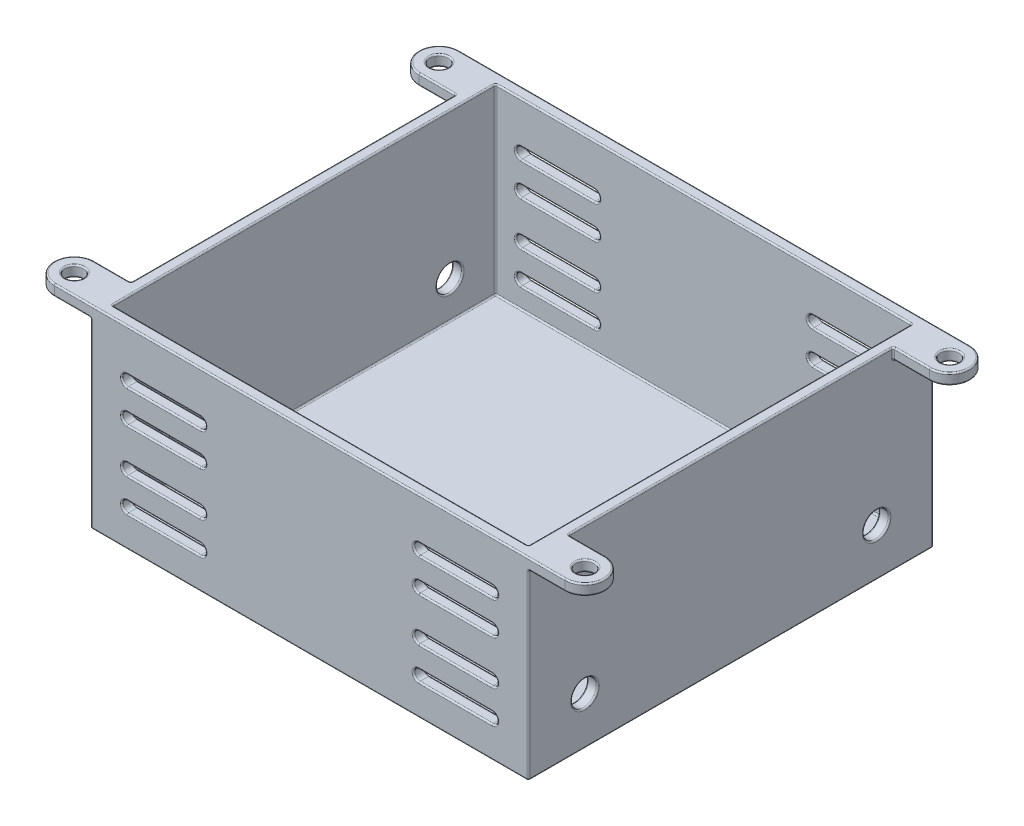
SolidWorks part; units mm, degrees
ref_plane "Front Plane" through (0, 0, 0) normal (0, 0, 1) x (1, 0, 0)
ref_plane "Top Plane" through (0, 0, 0) normal (0, 1, 0) x (1, 0, 0)
ref_plane "Right Plane" through (0, 0, 0) normal (1, 0, 0) x (0, 0, -1)
sketch "Sketch1" plane through (0, 0, 0) normal (0, 1, 0) x (1, 0, 0)
  line L0 (-35, 27.75) -> (35, 27.75) construction
  line L1 (-35, -25) -> (35, -25) construction
  line L2 (-35, -25) -> (-35, 25) construction
  line L3 (-35, 25) -> (35, 25) construction
  line L4 (35, -25) -> (35, 25) construction
  line L5 (-35, -25) -> (35, 25) construction
  line L6 (-35, 25) -> (35, -25) construction
  line L7 (-30, 27.75) -> (-30, -27.75)
  line L8 (-30, -27.75) -> (30, -27.75)
  line L9 (-35, -27.75) -> (35, -27.75) construction
  line L10 (30, -27.75) -> (30, 27.75)
  line L11 (30, 27.75) -> (-30, 27.75)
  line L12 (-35, 22.25) -> (-30, 22.25)
  line L13 (35, 22.25) -> (30, 22.25)
  line L14 (35, -22.25) -> (30, -22.25)
  line L15 (-35, -22.25) -> (-30, -22.25)
  circle A0 centre (-35, 25) radius 1.25
  circle A1 centre (-35, -25) radius 1.25
  circle A2 centre (35, -25) radius 1.25
  circle A3 centre (35, 25) radius 1.25
  circle A4 centre (-35, 25) radius 2.75
  circle A5 centre (35, 25) radius 2.75
  circle A6 centre (35, -25) radius 2.75
  circle A7 centre (-35, -25) radius 2.75
  point P0 (0, 0)
  point P22 (0, 27.75)
  dimension "D3" = 2.5
  dimension "D1" = 70
  dimension "D2" = 50
  dimension "D5" = 60
  dimension "D4" = 1.5
sketch "Sketch2" plane through (0, 0, 0) normal (0, 1, 0) x (1, 0, 0)
  line L0 (-30, -27.75) -> (30, -27.75) construction
  line L1 (30, -27.75) -> (30, 27.75) construction
  line L2 (-30, 27.75) -> (-30, -27.75) construction
  line L3 (30, 27.75) -> (-30, 27.75) construction
  line L4 (-30, -27.75) -> (30, -27.75)
  line L5 (30, -27.75) -> (30, 27.75)
  line L6 (-30, 27.75) -> (-30, -27.75)
  line L7 (30, 27.75) -> (-30, 27.75)
  line L8 (28.5, 26.25) -> (-28.5, 26.25)
  line L9 (-28.5, 26.25) -> (-28.5, -26.25)
  line L10 (-28.5, -26.25) -> (28.5, -26.25)
  line L11 (28.5, -26.25) -> (28.5, 26.25)
  dimension "D1" = 1.5
extrude "Boss-Extrude1" add sketch "Sketch2" against normal blind 25
sketch "Sketch3" plane through (0, -25, 0) normal (0, -1, 0) x (1, 0, 0)
  line L4 (-30, 27.75) -> (-30, -27.75)
  line L5 (-30, -27.75) -> (30, -27.75)
  line L6 (30, -27.75) -> (30, 27.75)
  line L7 (30, 27.75) -> (-30, 27.75)
  line L8 (-30, 27.75) -> (-30, -27.75)
  line L9 (-30, -27.75) -> (30, -27.75)
  line L10 (30, -27.75) -> (30, 27.75)
  line L11 (30, 27.75) -> (-30, 27.75)
  dimension "D1" = 0
extrude "Boss-Extrude2" add sketch "Sketch3" along normal blind 1.5
sketch "Sketch4" plane through (0, 0, 0) normal (0, 1, 0) x (1, 0, 0)
  line L0 (-35, -22.25) -> (-30, -22.25) construction
  line L1 (35, 22.25) -> (30, 22.25) construction
  line L2 (-35, 22.25) -> (-30, 22.25) construction
  line L3 (35, -22.25) -> (30, -22.25) construction
  line L4 (-30, 27.75) -> (-30, -27.75)
  line L5 (-30, -27.75) -> (30, -27.75)
  line L6 (30, -27.75) -> (30, 27.75)
  line L7 (30, 27.75) -> (-30, 27.75)
  line L8 (-30, 27.75) -> (-30, 22.25)
  line L10 (30, -27.75) -> (30, -22.25)
  line L12 (-35, -22.25) -> (-30, -22.25)
  line L13 (35, 22.25) -> (30, 22.25)
  line L14 (-35, 22.25) -> (-30, 22.25)
  line L15 (35, -22.25) -> (30, -22.25)
  line L16 (-35, 27.75) -> (35, 27.75) construction
  line L17 (-35, 27.75) -> (-30, 27.75)
  line L18 (-35, -27.75) -> (35, -27.75) construction
  line L19 (-35, -27.75) -> (-30, -27.75)
  line L20 (30, 22.25) -> (30, 27.75)
  line L21 (-30, -22.25) -> (-30, -27.75)
  line L22 (30, -27.75) -> (35, -27.75)
  line L23 (30, 27.75) -> (35, 27.75)
  circle A1 centre (35, -25) radius 2.75
  arc A2 (35, -27.75) -> (35, -22.25) centre (35, -25) ccw
  circle A3 centre (35, 25) radius 2.75
  arc A4 (35, 22.25) -> (35, 27.75) centre (35, 25) ccw
  circle A5 centre (-35, 25) radius 2.75
  arc A6 (-35, 27.75) -> (-35, 22.25) centre (-35, 25) ccw
  circle A7 centre (35, 25) radius 1.25
  circle A8 centre (35, 25) radius 1.25
  circle A9 centre (35, -25) radius 1.25
  circle A10 centre (35, -25) radius 1.25
  circle A11 centre (-35, -25) radius 1.25
  circle A12 centre (-35, -25) radius 1.25
  circle A13 centre (-35, 25) radius 1.25
  circle A14 centre (-35, 25) radius 1.25
  circle A15 centre (-35, -25) radius 2.75
  arc A16 (-35, -22.25) -> (-35, -27.75) centre (-35, -25) ccw
  dimension "D1" = 0
  dimension "D2" = 0
  dimension "D3" = 0
  dimension "D4" = 0
  dimension "D5" = 0
  dimension "D6" = 0
  dimension "D7" = 0
  dimension "D8" = 0
  dimension "D9" = 0
extrude "Boss-Extrude3" add sketch "Sketch4" against normal blind 1.5
sketch "Sketch5" plane through (0, 0, 0) normal (0, 0, 1) x (1, 0, 0)
  line L0 (30, -14) -> (-30, -14) construction
  line L1 (30, -26.5) -> (30, -1.5) construction
  line L2 (-30, -26.5) -> (-30, -1.5) construction
  line L3 (-25, -6.5) -> (-15, -6.5) construction
  line L4 (-25, -5.75) -> (-15, -5.75)
  line L5 (-25, -7.25) -> (-15, -7.25)
  line L6 (-25, -11) -> (-15, -11) construction
  line L7 (-25, -10.25) -> (-15, -10.25)
  line L8 (-25, -11.75) -> (-15, -11.75)
  line L9 (0, -14) -> (0, -20.2877) construction
  line L10 (25, -6.5) -> (15, -6.5) construction
  line L11 (25, -5.75) -> (15, -5.75)
  line L12 (25, -7.25) -> (15, -7.25)
  line L13 (25, -11) -> (15, -11) construction
  line L14 (25, -10.25) -> (15, -10.25)
  line L15 (25, -11.75) -> (15, -11.75)
  line L16 (25, -17) -> (15, -17) construction
  line L17 (25, -17.75) -> (15, -17.75)
  line L18 (25, -16.25) -> (15, -16.25)
  line L19 (-25, -17) -> (-15, -17) construction
  line L20 (-25, -17.75) -> (-15, -17.75)
  line L21 (-25, -16.25) -> (-15, -16.25)
  line L22 (25, -21.5) -> (15, -21.5) construction
  line L23 (25, -22.25) -> (15, -22.25)
  line L24 (25, -20.75) -> (15, -20.75)
  line L25 (-25, -21.5) -> (-15, -21.5) construction
  line L26 (-25, -22.25) -> (-15, -22.25)
  line L27 (-25, -20.75) -> (-15, -20.75)
  arc A0 (-25, -5.75) -> (-25, -7.25) centre (-25, -6.5) ccw
  arc A1 (-15, -7.25) -> (-15, -5.75) centre (-15, -6.5) ccw
  arc A2 (-25, -10.25) -> (-25, -11.75) centre (-25, -11) ccw
  arc A3 (-15, -11.75) -> (-15, -10.25) centre (-15, -11) ccw
  arc A4 (25, -5.75) -> (25, -7.25) centre (25, -6.5) cw
  arc A5 (15, -7.25) -> (15, -5.75) centre (15, -6.5) cw
  arc A6 (25, -10.25) -> (25, -11.75) centre (25, -11) cw
  arc A7 (15, -11.75) -> (15, -10.25) centre (15, -11) cw
  arc A8 (25, -17.75) -> (25, -16.25) centre (25, -17) ccw
  arc A9 (15, -16.25) -> (15, -17.75) centre (15, -17) ccw
  arc A10 (-25, -17.75) -> (-25, -16.25) centre (-25, -17) cw
  arc A11 (-15, -16.25) -> (-15, -17.75) centre (-15, -17) cw
  arc A12 (25, -22.25) -> (25, -20.75) centre (25, -21.5) ccw
  arc A13 (15, -20.75) -> (15, -22.25) centre (15, -21.5) ccw
  arc A14 (-25, -22.25) -> (-25, -20.75) centre (-25, -21.5) cw
  arc A15 (-15, -20.75) -> (-15, -22.25) centre (-15, -21.5) cw
  point P8 (-20, -6.5)
  point P16 (-20, -11)
  point P25 (20, -6.5)
  point P32 (20, -11)
  point P39 (20, -17)
  point P46 (-20, -17)
  point P53 (20, -21.5)
  point P60 (-20, -21.5)
  dimension "D1" = 10
  dimension "D2" = 1.5
  dimension "D3" = 20
  dimension "D4" = 7.5
  dimension "D5" = 4.5
extrude "Cut-Extrude4" cut sketch "Sketch5" along normal blind 53.5 and the other way blind 34.5
sketch "Sketch6" plane through (30, 0, 0) normal (1, 0, 0) x (0, 0, -1)
  line L0 (0, 0) -> (0, -20) construction
  line L1 (0, -20) -> (-20, -20) construction
  circle A0 centre (-20, -20) radius 1.75
  circle A1 centre (20, -20) radius 1.75
  dimension "D1" = 3.5
  dimension "D2" = 20
  dimension "D3" = 20
extrude "Cut-Extrude5" cut sketch "Sketch6" against normal blind 73.5
fillet "Fillet1" radius 0.2 196 edges at (30, -20, -18.25) (30, -20, 18.25) (-28.5, -20, -18.25) (28.5, -20, -21.75) (-30, -20, -18.25) (-28.5, -20, 21.75) (28.5, -20, 18.25) (-30, -20, 21.75) (-20, -7.25, 26.25) (-20, -7.25, 27.75) (-20, -7.25, -27.75) (-14.25, -6.5, 26.25) (-14.25, -6.5, 27.75) (-14.25, -6.5, -27.75) (-20, -5.75, 26.25) (-20, -5.75, 27.75) (-20, -5.75, -27.75) (-25.75, -6.5, 26.25) (-25.75, -6.5, 27.75) (-25.75, -6.5, -27.75) (-20, -17.75, 26.25) (-20, -17.75, 27.75) (-20, -17.75, -27.75) (-14.25, -17, 26.25) (-14.25, -17, 27.75) (-14.25, -17, -27.75) (-20, -16.25, 26.25) (-20, -16.25, 27.75) (-20, -16.25, -27.75) (-25.75, -17, 26.25) (-25.75, -17, 27.75) (-25.75, -17, -27.75) (20, -20.75, 26.25) (20, -20.75, 27.75) (20, -20.75, -27.75) (14.25, -21.5, 26.25) (14.25, -21.5, 27.75) (14.25, -21.5, -27.75) (20, -22.25, 26.25) (20, -22.25, 27.75) (20, -22.25, -27.75) (25.75, -21.5, 26.25) (25.75, -21.5, 27.75) (25.75, -21.5, -27.75) (-20, -22.25, 26.25) (-20, -22.25, 27.75) (-20, -22.25, -27.75) (-14.25, -21.5, 26.25) (-14.25, -21.5, 27.75) (-14.25, -21.5, -27.75) (-20, -20.75, 26.25) (-20, -20.75, 27.75) (-20, -20.75, -27.75) (-25.75, -21.5, 26.25) (-25.75, -21.5, 27.75) (-25.75, -21.5, -27.75) (-20, -11.75, 26.25) (-20, -11.75, 27.75) (-20, -11.75, -27.75) (-14.25, -11, 26.25) (-14.25, -11, 27.75) (-14.25, -11, -27.75) (-20, -10.25, 26.25) (-20, -10.25, 27.75) (-20, -10.25, -27.75) (-25.75, -11, 26.25) (-25.75, -11, 27.75) (-25.75, -11, -27.75) (20, -5.75, 26.25) (20, -5.75, 27.75) (20, -5.75, -27.75) (14.25, -6.5, 26.25) (14.25, -6.5, 27.75) (14.25, -6.5, -27.75) (20, -7.25, 26.25) (20, -7.25, 27.75) (20, -7.25, -27.75) (25.75, -6.5, 26.25) (25.75, -6.5, 27.75) (25.75, -6.5, -27.75) (20, -10.25, 26.25) (20, -10.25, 27.75) (20, -10.25, -27.75) (14.25, -11, 26.25) (14.25, -11, 27.75) (14.25, -11, -27.75) (20, -11.75, 26.25) (20, -11.75, 27.75) (20, -11.75, -27.75) (25.75, -11, 26.25) (25.75, -11, 27.75) (25.75, -11, -27.75) (20, -16.25, 26.25) (20, -16.25, 27.75) (20, -16.25, -27.75) (14.25, -17, 26.25) (14.25, -17, 27.75) (14.25, -17, -27.75) (20, -17.75, 26.25) (20, -17.75, 27.75) (20, -17.75, -27.75) (25.75, -17, 26.25) (25.75, -17, 27.75) (25.75, -17, -27.75) (35, -1.5, -23.75) (35, 0, -23.75) (32.5, 0, -22.25) (32.5, -1.5, -22.25) (37.75, 0, -25) (37.75, -1.5, -25) (32.5, -1.5, -27.75) (30, -1.5, -25) (30, -0.75, -22.25) (35, -1.5, 26.25) (35, 0, 26.25) (37.75, 0, 25) (37.75, -1.5, 25) (32.5, 0, 22.25) (32.5, -1.5, 22.25) (32.5, -1.5, 27.75) (30, -1.5, 25) (30, -0.75, 22.25) (-35, -1.5, 26.25) (-35, 0, 26.25) (-32.5, 0, 22.25) (-32.5, -1.5, 22.25) (-37.75, 0, 25) (-37.75, -1.5, 25) (-30, -1.5, 25) (-32.5, -1.5, 27.75) (-30, -0.75, 22.25) (-35, -1.5, -23.75) (-35, 0, -23.75) (-37.75, 0, -25) (-37.75, -1.5, -25) (-32.5, 0, -22.25) (-32.5, -1.5, -22.25) (-32.5, -1.5, -27.75) (-30, -1.5, -25) (-30, -0.75, -22.25) (0, -26.5, 27.75) (-30, -26.5, 0) (0, -26.5, -27.75) (30, -26.5, 0) (28.5, 0, 0) (28.5, -25, 0) (0, 0, -26.25) (0, -25, -26.25) (-28.5, 0, 0) (-28.5, -25, 0) (0, 0, 26.25) (0, -25, 26.25) (28.5, -12.5, -26.25) (-28.5, -12.5, -26.25) (-28.5, -12.5, 26.25) (28.5, -12.5, 26.25) (-30, 0, 0) (0, 0, 27.75) (30, 0, 0) (0, 0, -27.75) (-30, -14, 27.75) (30, -14, -27.75) (-30, -14, -27.75) (-20, -7.25, -26.25) (-14.25, -6.5, -26.25) (-20, -5.75, -26.25) (-25.75, -6.5, -26.25) (-20, -17.75, -26.25) (-14.25, -17, -26.25) (-20, -16.25, -26.25) (-25.75, -17, -26.25) (20, -20.75, -26.25) (14.25, -21.5, -26.25) (20, -22.25, -26.25) (25.75, -21.5, -26.25) (-20, -22.25, -26.25) (-14.25, -21.5, -26.25) (-20, -20.75, -26.25) (-25.75, -21.5, -26.25) (-20, -11.75, -26.25) (-14.25, -11, -26.25) (-20, -10.25, -26.25) (-25.75, -11, -26.25) (20, -5.75, -26.25) (14.25, -6.5, -26.25) (20, -7.25, -26.25) (25.75, -6.5, -26.25) (20, -10.25, -26.25) (14.25, -11, -26.25) (20, -11.75, -26.25) (25.75, -11, -26.25) (20, -16.25, -26.25) (14.25, -17, -26.25) (20, -17.75, -26.25) (25.75, -17, -26.25) (30, -14, 27.75)
